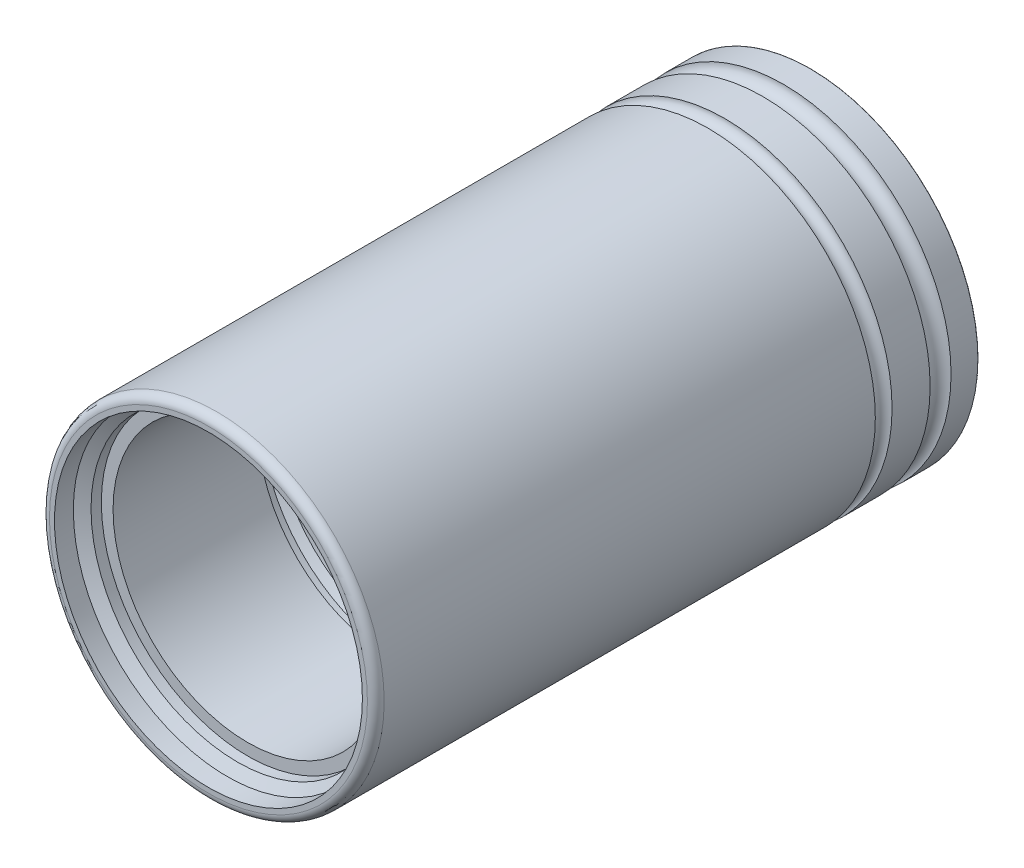
SolidWorks part; units mm, degrees
material "1.7319 (20MoCrS3)"
ref_plane "Спереди" through (0, 0, 0) normal (0, 0, 1) x (1, 0, 0)
ref_plane "Сверху" through (0, 0, 0) normal (0, 1, 0) x (1, 0, 0)
ref_plane "Справа" through (0, 0, 0) normal (1, 0, 0) x (0, 0, -1)
sketch "Эскиз1" plane through (0, 0, 0) normal (0, 0, 1) x (1, 0, 0)
  circle A0 centre (0, 0) radius 20
  dimension "D1" = 40
extrude "Бобышка-Вытянуть1" add sketch "Эскиз1" against normal blind 72
sketch "Эскиз4" plane through (0, 0, 0) normal (1, 0, 0) x (0, 0, -1)
  line L0 (0, 0) -> (0, 17.5)
  line L1 (0, 20) -> (0, -20) construction
  line L2 (0, 17.5) -> (4.7, 17.5)
  line L3 (4.7, 17.5) -> (4.7, 16.1)
  line L4 (4.7, 16.1) -> (22, 16.1)
  line L8 (22, 16.1) -> (22, 17.1)
  line L9 (22, 17.1) -> (23.4, 17.1)
  line L10 (23.4, 17.1) -> (23.9774, 16.1)
  line L14 (47, 6) -> (49, 6)
  line L15 (49, 6) -> (49, 9.5)
  line L16 (49, 9.5) -> (52.8, 9.5)
  line L20 (54, 9.5) -> (55.5, 9.5)
  line L21 (55.5, 9.5) -> (55.5, 10.75)
  line L22 (55.5, 10.75) -> (67, 10.75)
  line L23 (67, 10.75) -> (67, 12.4)
  line L24 (67, 12.4) -> (70, 12.4)
  line L25 (70, 12.4) -> (70, 10.75)
  line L26 (70, 10.75) -> (72, 10.75)
  line L27 (72, -20) -> (72, 20) construction
  line L28 (72, 10.75) -> (72, 0)
  line L29 (72, 0) -> (0, 0)
  line L32 (47, 16.1) -> (47, 6)
  line L33 (47, 16.1) -> (33.5, 16.1)
  line L35 (33.5, 16.1) -> (33.5, 18)
  line L36 (33.5, 18) -> (30.3, 18)
  line L37 (30.3, 16.1) -> (30.3, 18)
  line L38 (30.3, 16.1) -> (23.9774, 16.1)
  arc A0 (52.8, 9.5) -> (54, 9.5) centre (53.4, 9.5) cw
  dimension "D8" = 0.6
  dimension "D1" = 10.75
  dimension "D2" = 12.4
  dimension "D3" = 2
  dimension "D4" = 3
  dimension "D5" = 16.5
  dimension "D6" = 2.1
  dimension "D7" = 9.5
  dimension "D9" = 17.1
  dimension "D10" = 2
  dimension "D11" = 13.5
  dimension "D12" = 17.5
  dimension "D13" = 3.2
  dimension "D14" = 4.7
  dimension "D15" = 1.9
  dimension "D16" = 60
  dimension "D17" = 16.1
  dimension "D18" = 6
  dimension "D19" = 1.4
  dimension "D20" = 23
  dimension "D21" = 22
revolve "Вырез-Повернуть1" cut sketch "Эскиз4" angle 360 about L29
sketch "Эскиз5" plane through (0, 0, 0) normal (1, 0, 0) x (0, 0, -1)
  line L0 (3.466, 17.5) -> (1.734, 17.5)
  line L1 (1.734, 17.5) -> (2.6, 19)
  line L2 (2.6, 19) -> (3.466, 17.5)
  line L3 (4.7, 17.5) -> (4.7, -17.5) construction
  line L4 (4.7, 17.5) -> (4.7, -17.5) construction
  line L5 (0, 17.5) -> (0, -17.5) construction
  line L6 (0, 0) -> (8.2655, 0) construction
  line L7 (0, 20) -> (0, -20) construction
  line L8 (0, 20) -> (0, -20) construction
  point P3 (2.6, 17.5)
  dimension "D1" = 1
  dimension "D2" = 60
  dimension "D3" = 2.6
revolve "Вырез-Повернуть2" cut sketch "Эскиз5" angle 360 about L6
fillet "Скругление2" radius 1 1 edges at (20, 0, 0)
sketch "Эскиз6" plane through (0, 0, 0) normal (0, 0, 1) x (1, 0, 0)
  circle A2 centre (0, 0) radius 18.4
  dimension "D1" = 36.8
extrude "Вырез-Вытянуть1" cut sketch "Эскиз6" against normal blind 2.6
fillet "Скругление3" radius 0.05 3 edges at (-10.75, 0, -72) (20, 0, -72) (-6, 0, -49)
fillet "Скругление4" [suppressed] radius 0.1
fillet "Скругление5" [suppressed] radius 0.2
fillet "Скругление6" [suppressed] radius 0.4
fillet "Скругление7" [suppressed] radius 0.2
sketch "Эскиз7" plane through (0, 0, 0) normal (0, 1, 0) x (1, 0, 0)
  line L0 (19.95, 72) -> (-19.95, 72) construction
  line L2 (0, 88.9589) -> (0, 57.4428) construction
  line L7 (-35.75, 52) -> (-35.75, 72.9) construction
  line L8 (-14.75, 93.9) -> (-13.85, 93.9) construction
  line L9 (7.15, 72.9) -> (7.15, 52) construction
  line L10 (-35.75, 52) -> (7.15, 52) construction
  line L14 (-14.5, 72) -> (-15.95, 72)
  line L15 (-15.95, 72) -> (-15.95, 72.8984)
  line L16 (-14.95, 73.8984) -> (-14.5, 73.8984)
  line L17 (-14.5, 73.8984) -> (-14.0476, 73.8984)
  line L18 (-13.0476, 72.8984) -> (-13.0476, 72)
  line L19 (-13.0476, 72) -> (-14.5, 72)
  arc A3 (-14.75, 93.9) -> (-35.75, 72.9) centre (-14.75, 72.9) ccw construction
  arc A4 (-13.85, 93.9) -> (7.15, 72.9) centre (-13.85, 72.9) cw construction
  arc A7 (-13.0476, 72.8984) -> (-14.0476, 73.8984) centre (-14.0476, 72.8984) ccw
  arc A8 (-15.95, 72.8984) -> (-14.95, 73.8984) centre (-14.95, 72.8984) cw
  point P14 (0, 0)
  dimension "D3" = 1
  dimension "D2" = 14.5
revolve "Повернуть1" add sketch "Эскиз7" angle 360 about L2
sketch "Эскиз8" plane through (0, 0, 0) normal (1, 0, 0) x (0, 0, -1)
  line L0 (1, -20) -> (1, 20) construction
  line L1 (1, -20) -> (1, 20) construction
  line L2 (67.5, 20) -> (40.6285, 20) construction
  line L7 (0, 0) -> (74.6339, 0) construction
  line L8 (72, -19.95) -> (72, 19.95) construction
  line L9 (72, -19.95) -> (72, 19.95) construction
  line L10 (71.95, 20) -> (1, 20) construction
  circle A0 centre (67.5, 20) radius 1.25
  circle A1 centre (60.7, 20) radius 1
  dimension "D1" = 2.5
  dimension "D3" = 2
  dimension "D4" = 6.8
  dimension "D2" = 4.5
  dimension "D5" = 20
revolve "Вырез-Повернуть3" cut sketch "Эскиз8" angle 360 about L7
fillet "Скругление10" [suppressed] radius 0.2
fillet "Скругление11" [suppressed] radius 0.2
